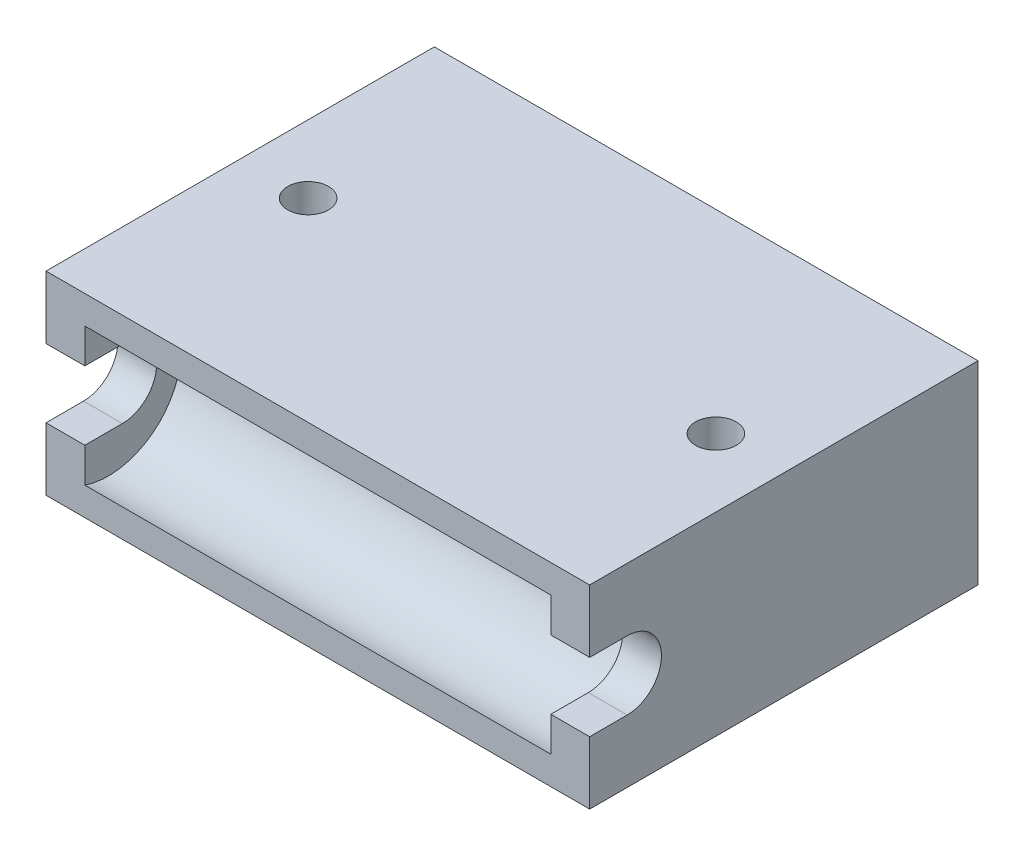
SolidWorks part; units mm, degrees
ref_plane "Спереди" through (0, 0, 0) normal (0, 0, 1) x (1, 0, 0)
ref_plane "Сверху" through (0, 0, 0) normal (0, 1, 0) x (1, 0, 0)
ref_plane "Справа" through (0, 0, 0) normal (1, 0, 0) x (0, 0, -1)
sketch "Эскиз1" plane through (0, 0, 0) normal (0, 1, 0) x (1, 0, 0)
  line L1 (-32.2176, -1.5533) -> (23.7824, -1.5533)
  line L2 (-32.2176, -1.5533) -> (-32.2176, -41.5533)
  line L3 (-32.2176, -41.5533) -> (23.7824, -41.5533)
  line L4 (23.7824, -1.5533) -> (23.7824, -41.5533)
extrude "Бобышка-Вытянуть1" add sketch "Эскиз1" along normal blind 20 contours L4 L3 L2 L1
ref_plane "Плоскость1" through (-28.2176, 0, 0) normal (-1, 0, 0) x (0, 0, 1)
sketch "Эскиз2" plane through (-28.2176, 0, 0) normal (-1, 0, 0) x (0, 0, 1)
  line L0 (21.5533, -3.5565) -> (41.5533, -3.5565) construction
  circle A0 centre (39.1357, 10) radius 7.5
  dimension "D1" = 15
extrude "Вырез-Вытянуть1" cut sketch "Эскиз2" against normal blind 48
sketch "Эскиз4" plane through (19.7824, 0, 0) normal (-1, 0, 0) x (0, 0, 1)
  line L0 (37.6937, 13.535) -> (41.5533, 13.535)
  line L1 (41.5533, 2.9003) -> (41.5533, 17.0997) construction
  line L2 (37.6937, 6.465) -> (41.5533, 6.465)
  line L3 (41.5533, 13.535) -> (41.5533, 6.465)
  arc A0 (37.6937, 13.535) -> (37.6937, 6.465) centre (37.6937, 10) ccw
  dimension "D1" = 7.07
extrude "Вырез-Вытянуть2" cut sketch "Эскиз4" against normal blind 48 and the other way through all
sketch "Эскиз5" plane through (0, 0, 1.5533) normal (0, 0, -1) x (-1, 0, 0)
  line L0 (-23.7824, -4.9614) -> (32.2176, -4.9614) construction
  line L1 (32.2176, -4.9614) -> (32.2176, 10) construction
  line L2 (32.2176, 20) -> (32.2176, 0) construction
  line L3 (-23.7824, -7.1872) -> (4.2176, -7.1872) construction
  line L4 (-23.7824, -9.6662) -> (-9.7824, -9.6662) construction
  line L5 (32.2176, -7.1872) -> (4.2176, -7.1872) construction
  line L6 (32.2176, -9.6662) -> (18.2176, -9.6662) construction
  circle A0 centre (-16.7824, 10) radius 4.15
  circle A1 centre (25.2176, 10) radius 4.15
  dimension "D1" = 8.3
  dimension "D2" = 8.3
  dimension "D3" = 42
extrude "Вырез-Вытянуть3" cut sketch "Эскиз5" against normal blind 10
sketch "Эскиз6" plane through (0, 20, 0) normal (0, 1, 0) x (1, 0, 0)
  line L0 (-32.2176, -45.0305) -> (23.7824, -45.0305) construction
  line L1 (-32.2176, -43.0907) -> (-4.2176, -43.0907) construction
  line L2 (-32.2176, -43.9246) -> (-18.2176, -43.9246) construction
  line L3 (23.7824, -43.0907) -> (-4.2176, -43.0907) construction
  line L4 (23.7824, -43.9246) -> (9.7824, -43.9246) construction
  circle A0 centre (-25.2176, -21.5533) radius 2.1
  circle A1 centre (16.7824, -21.5533) radius 2.1
  dimension "D1" = 4.2
  dimension "D2" = 4.2
extrude "Вырез-Вытянуть4" cut sketch "Эскиз6" against normal through all
sketch "Эскиз7" plane through (0, 0, 0) normal (0, -1, 0) x (1, 0, 0)
  line L1 (-21.1761, 21.5533) -> (-23.1968, 25.0533)
  line L2 (-23.1968, 25.0533) -> (-27.2383, 25.0533)
  line L3 (-27.2383, 25.0533) -> (-29.259, 21.5533)
  line L4 (-29.259, 21.5533) -> (-27.2383, 18.0533)
  line L5 (-27.2383, 18.0533) -> (-23.1968, 18.0533)
  line L6 (-23.1968, 18.0533) -> (-21.1761, 21.5533)
  line L7 (20.8239, 21.5533) -> (18.8032, 25.0533)
  line L8 (18.8032, 25.0533) -> (14.7617, 25.0533)
  line L9 (14.7617, 25.0533) -> (12.741, 21.5533)
  line L10 (12.741, 21.5533) -> (14.7617, 18.0533)
  line L11 (14.7617, 18.0533) -> (18.8032, 18.0533)
  line L12 (18.8032, 18.0533) -> (20.8239, 21.5533)
  circle A0 centre (-25.2176, 21.5533) radius 3.5 construction
  circle A1 centre (16.7824, 21.5533) radius 3.5 construction
extrude "Вырез-Вытянуть5" cut sketch "Эскиз7" against normal blind 10
